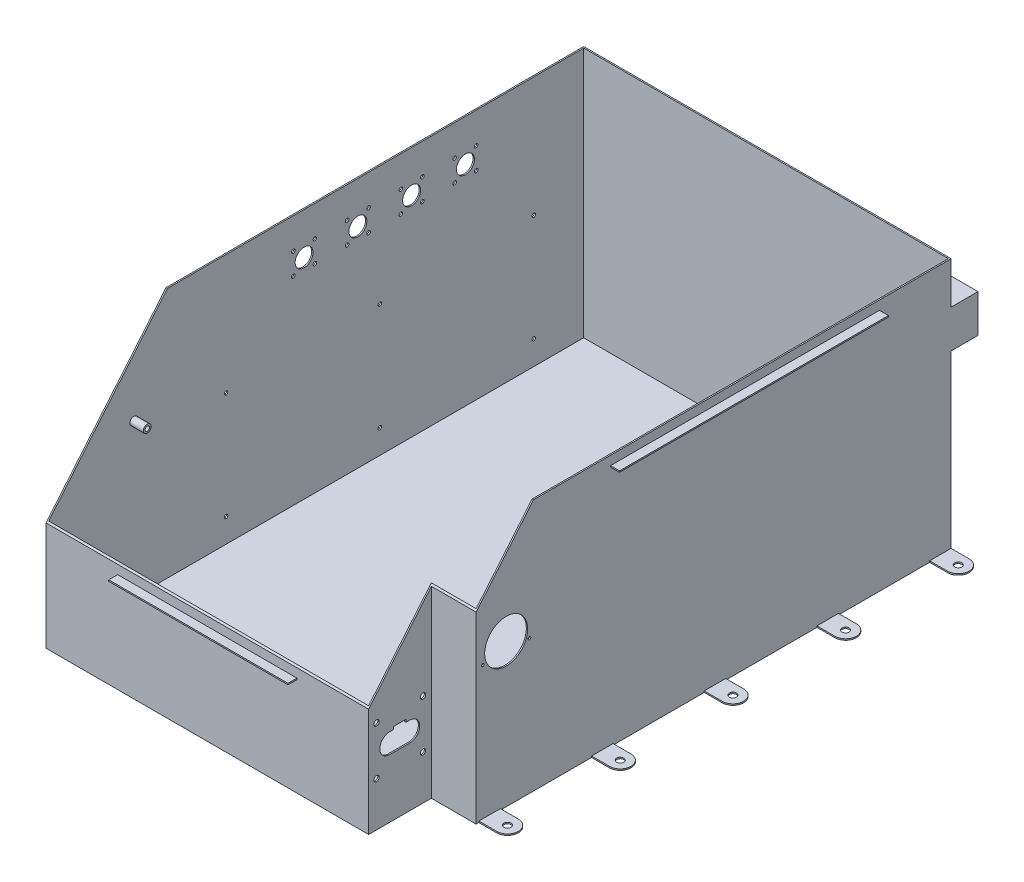
SolidWorks part; units mm, degrees
ref_plane "Front Plane" through (0, 0, 0) normal (0, 0, 1) x (1, 0, 0)
ref_plane "Top Plane" through (0, 0, 0) normal (0, 1, 0) x (1, 0, 0)
ref_plane "Right Plane" through (0, 0, 0) normal (1, 0, 0) x (0, 0, -1)
sketch "Sketch1" plane through (0, 0, 0) normal (0, 1, 0) x (1, 0, 0)
  line L1 (-205, 237.8263) -> (205, 237.8263)
  line L2 (-205, 237.8263) -> (-205, -362.1737)
  line L3 (-205, -362.1737) -> (155, -362.1737)
  line L4 (205, 237.8263) -> (205, -292.1737)
  line L6 (205, -292.1737) -> (155, -292.1737)
  line L7 (155, -292.1737) -> (155, -362.1737)
  line L8 (0, -55) -> (0, 55) construction
  point P1 (0, 237.8263)
  dimension "D1" = 600
  dimension "D2" = 410
  dimension "D5" = 70
  dimension "D6" = 50
extrude "Boss-Extrude1" add sketch "Sketch1" along normal blind 1.5
sketch "Sketch2" plane through (0, 1.5, 0) normal (0, 1, 0) x (1, 0, 0)
  line L60 (-203.5, 236.3263) -> (-203.5, -360.6737)
  line L61 (-203.5, -360.6737) -> (153.5, -360.6737)
  line L62 (153.5, -360.6737) -> (153.5, -290.6737)
  line L63 (153.5, -290.6737) -> (203.5, -290.6737)
  line L64 (203.5, -290.6737) -> (203.5, 236.3263)
  line L65 (203.5, 236.3263) -> (-203.5, 236.3263)
  line L66 (-205, 237.8263) -> (-205, -362.1737)
  line L67 (-205, -362.1737) -> (155, -362.1737)
  line L68 (155, -362.1737) -> (155, -292.1737)
  line L69 (155, -292.1737) -> (205, -292.1737)
  line L70 (205, -292.1737) -> (205, 237.8263)
  line L71 (205, 237.8263) -> (-205, 237.8263)
  line L72 (-205, 237.8263) -> (-205, -362.1737)
  line L73 (-205, -362.1737) -> (155, -362.1737)
  line L74 (155, -362.1737) -> (155, -292.1737)
  line L75 (155, -292.1737) -> (205, -292.1737)
  line L76 (205, -292.1737) -> (205, 237.8263)
  line L77 (205, 237.8263) -> (-205, 237.8263)
  dimension "D1" = 0
  dimension "D2" = 1.5
extrude "Boss-Extrude2" add sketch "Sketch2" along normal blind 280
sketch "Sketch3" plane through (-205, 0, 0) normal (-1, 0, 0) x (0, 0, 1)
  line L3 (362.1737, 281.5) -> (362.1737, 0) construction
  line L4 (362.1737, 121.1176) -> (228.1952, 281.5)
  line L6 (-237.8263, 281.5) -> (362.1737, 281.5) construction
  line L9 (362.1737, 281.5) -> (362.1737, 121.1176)
  line L10 (228.1952, 281.5) -> (362.1737, 281.5)
sketch "Sketch4" plane through (0, 0, -237.8263) normal (0, 0, -1) x (-1, 0, 0)
  line L0 (-205, 281.5) -> (-205, 0) construction
  line L1 (-205, 234.6761) -> (205, 234.6761)
  line L2 (-205, 234.6761) -> (-205, 192.2905)
  line L3 (-205, 192.2905) -> (205, 192.2905)
  line L4 (205, 234.6761) -> (205, 192.2905)
  line L5 (205, 281.5) -> (205, 0) construction
extrude "Boss-Extrude3" add sketch "Sketch4" along normal blind 30
extrude "Cut-Extrude1" cut sketch "Sketch3" against normal through all both and the other way through all
sketch "Sketch5" plane through (-205, 0, 0) normal (-1, 0, 0) x (0, 0, 1)
  line L0 (-116.3263, 223.1259) -> (-116.3263, 247.1259) construction
  line L5 (-116.3263, 223.1259) -> (-92.3263, 223.1259) construction
  line L6 (-116.3263, 247.1259) -> (-92.3263, 247.1259) construction
  line L7 (-92.3263, 223.1259) -> (-92.3263, 247.1259) construction
  line L8 (-116.3263, 223.1259) -> (-92.3263, 247.1259) construction
  line L9 (-116.3263, 247.1259) -> (-92.3263, 223.1259) construction
  line L10 (-56.3263, 223.1259) -> (-56.3263, 247.1259) construction
  line L11 (-56.3263, 223.1259) -> (-32.3263, 223.1259) construction
  line L12 (-56.3263, 247.1259) -> (-32.3263, 247.1259) construction
  line L13 (-32.3263, 223.1259) -> (-32.3263, 247.1259) construction
  line L14 (-56.3263, 223.1259) -> (-32.3263, 247.1259) construction
  line L15 (-56.3263, 247.1259) -> (-32.3263, 223.1259) construction
  line L16 (3.6737, 223.1259) -> (3.6737, 247.1259) construction
  line L17 (3.6737, 223.1259) -> (27.6737, 223.1259) construction
  line L18 (3.6737, 247.1259) -> (27.6737, 247.1259) construction
  line L19 (27.6737, 223.1259) -> (27.6737, 247.1259) construction
  line L20 (3.6737, 223.1259) -> (27.6737, 247.1259) construction
  line L21 (3.6737, 247.1259) -> (27.6737, 223.1259) construction
  line L22 (63.6737, 223.1259) -> (63.6737, 247.1259) construction
  line L23 (63.6737, 223.1259) -> (87.6737, 223.1259) construction
  line L24 (63.6737, 247.1259) -> (87.6737, 247.1259) construction
  line L25 (87.6737, 223.1259) -> (87.6737, 247.1259) construction
  line L26 (63.6737, 223.1259) -> (87.6737, 247.1259) construction
  line L27 (63.6737, 247.1259) -> (87.6737, 223.1259) construction
  line L28 (-236.3263, 281.5) -> (-236.3263, 1.5) construction
  circle A0 centre (-116.3263, 247.1259) radius 2
  circle A1 centre (-116.3263, 223.1259) radius 2
  circle A2 centre (-92.3263, 223.1259) radius 2
  circle A3 centre (-92.3263, 247.1259) radius 2
  circle A4 centre (-104.3263, 235.1259) radius 10
  circle A5 centre (-56.3263, 247.1259) radius 2
  circle A6 centre (-56.3263, 223.1259) radius 2
  circle A7 centre (-32.3263, 223.1259) radius 2
  circle A8 centre (-32.3263, 247.1259) radius 2
  circle A9 centre (-44.3263, 235.1259) radius 10
  circle A10 centre (3.6737, 247.1259) radius 2
  circle A11 centre (3.6737, 223.1259) radius 2
  circle A12 centre (27.6737, 223.1259) radius 2
  circle A13 centre (27.6737, 247.1259) radius 2
  circle A14 centre (15.6737, 235.1259) radius 10
  circle A15 centre (63.6737, 247.1259) radius 2
  circle A16 centre (63.6737, 223.1259) radius 2
  circle A17 centre (87.6737, 223.1259) radius 2
  circle A18 centre (87.6737, 247.1259) radius 2
  circle A19 centre (75.6737, 235.1259) radius 10
  point P9 (-104.3263, 235.1259)
  point P24 (-44.3263, 235.1259)
  point P38 (15.6737, 235.1259)
  point P52 (75.6737, 235.1259)
  dimension "D2" = 20
  dimension "D5" = 4
  dimension "D1" = 24
  dimension "D3" = 24
  dimension "D4" = 24
  dimension "D7" = 120
  dimension "D6" = 4
sketch "Sketch6" plane through (-203.5, 0, 0) normal (1, 0, 0) x (0, 0, -1)
  arc A0 (151.1392, 167.4539) -> (156.7272, 167.4539) centre (153.9332, 167.4539) ccw construction
  arc A1 (-68.8756, 167.4539) -> (-63.2876, 167.4539) centre (-66.0816, 167.4539) ccw construction
  arc A2 (-178.883, 167.4539) -> (-173.295, 167.4539) centre (-176.089, 167.4539) ccw construction
  arc A3 (151.1392, 167.4539) -> (156.7272, 167.4539) centre (153.9332, 167.4539) ccw
  arc A4 (-68.8756, 167.4539) -> (-63.2876, 167.4539) centre (-66.0816, 167.4539) ccw
  arc A5 (-178.883, 167.4539) -> (-173.295, 167.4539) centre (-176.089, 167.4539) ccw
  circle A6 centre (-176.089, 167.4539) radius 2.794
  circle A7 centre (-176.089, 167.4539) radius 4.5
  circle A8 centre (-64.4633, 167.4539) radius 4.5
  circle A9 centre (-64.4633, 167.4539) radius 2.794
  circle A10 centre (155.5515, 167.4539) radius 2.794
  circle A11 centre (155.5515, 167.4539) radius 4.5
  dimension "D1" = 9
extrude "Boss-Extrude4" [suppressed] add sketch "Sketch6" along normal blind 50 contours A4 A9 | A8 | A7 | A6 | A11 | A10
sketch "Sketch8" plane through (-203.5, 0, 0) normal (1, 0, 0) x (0, 0, -1)
  line L0 (236.3263, 1.5) -> (-360.6737, 1.5) construction
  line L1 (-360.6737, 122.9132) -> (-360.6737, 1.5) construction
  circle A0 centre (-265.6737, 172.2) radius 2.39
  circle A1 centre (-265.6737, 172.2) radius 4.39
  circle A2 centre (-265.6737, 16.5) radius 2.39
  circle A3 centre (-265.6737, 16.5) radius 4.39
  dimension "D3" = 4.78
  dimension "D4" = 2
  dimension "D1" = 155.7
  dimension "D2" = 15
  dimension "D5" = 95
extrude "Boss-Extrude5" add sketch "Sketch8" along normal blind 15
sketch "Sketch10" plane through (153.5, 0, 0) normal (-1, 0, 0) x (0, 0, 1)
  line L0 (316.1737, 86.5) -> (321.4237, 86.5) construction
  line L1 (316.1737, 66.5) -> (338.6737, 66.5) construction
  line L2 (338.6737, 76.5) -> (316.1737, 76.5) construction
  line L3 (360.6737, 1.5) -> (290.6737, 1.5) construction
  line L5 (321.4237, 86.5) -> (321.4237, 89.5) construction
  line L6 (321.4237, 89.5) -> (333.4237, 89.5) construction
  line L7 (333.4237, 86.5) -> (333.4237, 89.5) construction
  line L8 (360.6737, 122.9132) -> (360.6737, 1.5) construction
  line L9 (333.4237, 86.5) -> (338.6737, 86.5) construction
  line L10 (320.4237, 90.5) -> (334.4237, 90.5)
  line L11 (334.4237, 87.5) -> (334.4237, 90.5)
  line L12 (334.4237, 87.5) -> (338.6737, 87.5)
  line L13 (316.1737, 65.5) -> (338.6737, 65.5)
  line L14 (316.1737, 87.5) -> (320.4237, 87.5)
  line L15 (320.4237, 87.5) -> (320.4237, 90.5)
  line L17 (301.4737, 49.55) -> (353.3737, 49.55) construction
  line L18 (301.4737, 49.55) -> (301.4737, 103.45) construction
  line L19 (301.4737, 103.45) -> (353.3737, 103.45) construction
  line L20 (353.3737, 49.55) -> (353.3737, 103.45) construction
  line L21 (301.4737, 49.55) -> (353.3737, 103.45) construction
  line L22 (301.4737, 103.45) -> (353.3737, 49.55) construction
  arc A0 (316.1737, 86.5) -> (316.1737, 66.5) centre (316.1737, 76.5) ccw construction
  arc A1 (338.6737, 66.5) -> (338.6737, 86.5) centre (338.6737, 76.5) ccw construction
  arc A2 (338.6737, 65.5) -> (338.6737, 87.5) centre (338.6737, 76.5) ccw
  arc A3 (316.1737, 87.5) -> (316.1737, 65.5) centre (316.1737, 76.5) ccw
  circle A4 centre (301.4737, 103.45) radius 3
  circle A5 centre (353.3737, 103.45) radius 3
  circle A6 centre (301.4737, 49.55) radius 3
  circle A7 centre (353.3737, 49.55) radius 3
  point P12 (327.4237, 89.5)
  point P13 (327.4237, 76.5)
  point P26 (327.4237, 76.5)
  dimension "D1" = 65
  dimension "D2" = 22.5
  dimension "D6" = 20
  dimension "D10" = 6
  dimension "D3" = 22
  dimension "D4" = 12
  dimension "D5" = 3
  dimension "D8" = 51.9
  dimension "D9" = 53.9
  dimension "D7" = 1
extrude "Cut-Extrude2" cut sketch "Sketch10" against normal up to surface (1.5 mm away)
sketch "Sketch11" plane through (153.5, 0, 0) normal (-1, 0, 0) x (0, 0, 1)
  line L0 (298.4737, 103.43) -> (298.4737, 49.53) construction
  line L13 (316.1737, 66.5) -> (338.6737, 66.5) construction
  line L14 (316.1737, 86.5) -> (321.4237, 86.5) construction
  line L15 (316.1737, 66.5) -> (338.6737, 66.5)
  line L19 (316.1737, 86.5) -> (318.4237, 86.5)
  line L20 (334.4237, 90.5) -> (320.4237, 90.5)
  line L21 (334.4237, 90.5) -> (320.4237, 90.5)
  line L22 (334.4237, 87.5) -> (334.4237, 90.5)
  line L23 (334.4237, 87.5) -> (334.4237, 90.5)
  line L28 (330.4237, 86.5) -> (321.4237, 86.5)
  line L29 (316.2509, 66) -> (338.7144, 66)
  line L30 (330.9237, 86) -> (320.7529, 86)
  line L31 (330.9237, 86) -> (330.9237, 91)
  line L32 (330.9237, 91) -> (317.9237, 91)
  line L33 (317.9237, 91) -> (317.9237, 87)
  line L34 (316.2509, 87) -> (317.9237, 87)
  line L36 (298.4737, 103.43) -> (350.3737, 103.43) construction
  line L43 (334.4237, 90.5) -> (320.4237, 90.5)
  line L44 (334.4237, 90.5) -> (320.4237, 90.5)
  line L45 (334.4237, 87.5) -> (334.4237, 90.5)
  line L46 (334.4237, 87.5) -> (334.4237, 90.5)
  line L47 (338.6737, 87.5) -> (334.4237, 87.5)
  line L48 (338.6737, 87.5) -> (334.4237, 87.5)
  line L49 (316.1737, 65.5) -> (338.6737, 65.5)
  line L50 (316.1737, 65.5) -> (338.6737, 65.5)
  line L51 (320.4237, 87.5) -> (316.1737, 87.5)
  line L52 (320.4237, 87.5) -> (316.1737, 87.5)
  line L53 (320.4237, 90.5) -> (320.4237, 87.5)
  line L54 (320.4237, 90.5) -> (320.4237, 87.5)
  line L55 (334.4237, 90.5) -> (320.4237, 90.5)
  line L56 (334.4237, 90.5) -> (320.4237, 90.5)
  line L57 (334.4237, 87.5) -> (334.4237, 90.5)
  line L58 (334.4237, 87.5) -> (334.4237, 90.5)
  line L59 (338.6737, 87.5) -> (334.4237, 87.5)
  line L60 (338.6737, 87.5) -> (334.4237, 87.5)
  line L61 (316.1737, 65.5) -> (338.6737, 65.5)
  line L62 (316.1737, 65.5) -> (338.6737, 65.5)
  line L63 (320.4237, 87.5) -> (316.1737, 87.5)
  line L64 (320.4237, 87.5) -> (316.1737, 87.5)
  line L65 (320.4237, 90.5) -> (320.4237, 87.5)
  line L66 (320.4237, 90.5) -> (320.4237, 87.5)
  line L67 (330.4237, 86.5) -> (330.4237, 90.5) construction
  line L68 (330.4237, 90.5) -> (318.4237, 90.5) construction
  line L69 (318.4237, 90.5) -> (318.4237, 86.5) construction
  line L70 (338.6737, 87.5) -> (334.4237, 87.5)
  line L71 (338.6737, 87.5) -> (334.4237, 87.5)
  line L72 (316.1737, 65.5) -> (338.6737, 65.5)
  line L73 (316.1737, 65.5) -> (338.6737, 65.5)
  line L74 (320.4237, 87.5) -> (316.1737, 87.5)
  line L75 (320.4237, 87.5) -> (316.1737, 87.5)
  line L76 (320.4237, 90.5) -> (320.4237, 87.5)
  line L77 (320.4237, 90.5) -> (320.4237, 87.5)
  arc A4 (338.7144, 66) -> (320.7529, 86) centre (336.1498, 81.7622) ccw
  arc A5 (338.6737, 65.5) -> (338.6737, 87.5) centre (338.6737, 76.5) ccw
  arc A7 (338.6737, 65.5) -> (338.6737, 87.5) centre (338.6737, 76.5) ccw
  arc A9 (316.2509, 87) -> (316.2509, 66) centre (312.9721, 76.5) ccw
  circle A10 centre (298.4737, 103.43) radius 3
  circle A11 centre (298.4737, 49.53) radius 3
  circle A12 centre (350.3737, 103.43) radius 3
  circle A13 centre (350.3737, 49.53) radius 3
  arc A16 (338.6737, 66.5) -> (321.4237, 86.5) centre (336.1498, 81.7622) ccw construction
  arc A17 (338.6737, 65.5) -> (338.6737, 87.5) centre (338.6737, 76.5) ccw
  arc A18 (316.1737, 87.5) -> (316.1737, 65.5) centre (316.1737, 76.5) ccw
  arc A19 (316.1737, 87.5) -> (316.1737, 65.5) centre (316.1737, 76.5) ccw
  arc A20 (316.1737, 86.5) -> (316.1737, 66.5) centre (312.9721, 76.5) ccw construction
  arc A21 (338.6737, 65.5) -> (338.6737, 87.5) centre (338.6737, 76.5) ccw
  arc A22 (316.1737, 87.5) -> (316.1737, 65.5) centre (316.1737, 76.5) ccw
  arc A23 (316.1737, 87.5) -> (316.1737, 65.5) centre (316.1737, 76.5) ccw
  arc A24 (338.6737, 65.5) -> (338.6737, 87.5) centre (338.6737, 76.5) ccw
  arc A25 (338.6737, 65.5) -> (338.6737, 87.5) centre (338.6737, 76.5) ccw
  arc A26 (316.1737, 87.5) -> (316.1737, 65.5) centre (316.1737, 76.5) ccw
  arc A27 (316.1737, 87.5) -> (316.1737, 65.5) centre (316.1737, 76.5) ccw
  dimension "D5" = 6
  dimension "D6" = 51.9
  dimension "D7" = 53.9
  dimension "D1" = 0
  dimension "D2" = 0
  dimension "D3" = 0
  dimension "D4" = 0.5
extrude "Cut-Extrude3" [suppressed] cut sketch "Sketch11" against normal through all
sketch "Sketch14" plane through (153.5, 0, 0) normal (-1, 0, 0) x (0, 0, 1)
  line L0 (362.1737, 121.1176) -> (362.1737, 0) construction
  line L1 (362.1737, 0) -> (292.1737, 0) construction
  circle A0 centre (297.2737, 103.43) radius 3
  circle A1 centre (349.1737, 103.43) radius 3
  circle A2 centre (349.1737, 49.53) radius 3
  circle A3 centre (297.2737, 49.53) radius 3
  dimension "D5" = 6
  dimension "D1" = 51.9
  dimension "D2" = 53.9
  dimension "D3" = 13
  dimension "D4" = 103.43
extrude "Cut-Extrude4" [suppressed] cut sketch "Sketch14" against normal up to surface (1.5 mm away)
sketch "Sketch15" plane through (203.5, 0, 0) normal (-1, 0, 0) x (0, 0, 1)
  line L1 (-151.3263, 252.1363) -> (-136.3263, 252.1363)
  line L2 (-151.3263, 252.1363) -> (-151.3263, 250.6363)
  line L3 (-151.3263, 250.6363) -> (-136.3263, 250.6363)
  line L4 (-136.3263, 252.1363) -> (-136.3263, 250.6363)
  line L5 (-236.3263, 281.5) -> (-236.3263, 1.5) construction
  line L6 (126.6737, 252.1363) -> (146.6737, 252.1363)
  line L7 (126.6737, 250.6363) -> (146.6737, 250.6363)
  line L8 (126.6737, 252.1363) -> (126.6737, 250.6363)
  line L9 (146.6737, 252.1363) -> (146.6737, 250.6363)
  dimension "D1" = 1.5
  dimension "D2" = 15
  dimension "D3" = 85
  dimension "D4" = 363
  dimension "D5" = 20
extrude "Boss-Extrude6" add sketch "Sketch15" along normal blind 13
ref_plane "Plane1" through (0, 0, -131.3263) normal (0, 0, -1) x (-1, 0, 0)
sketch "Sketch17" plane through (0, 0, -136.3263) normal (0, 0, 1) x (1, 0, 0)
  line L0 (203.5, 250.6363) -> (203.5, 235.6363)
  line L1 (203.5, 281.5) -> (203.5, 206.7085) construction
  line L2 (203.5, 235.6363) -> (190.5, 250.6363)
  line L3 (190.5, 250.6363) -> (203.5, 250.6363)
  dimension "D1" = 15
extrude "Boss-Extrude7" add sketch "Sketch17" against normal blind 1.5
ref_plane "Plane2" through (0, 0, 126.6737) normal (0, 0, 1) x (1, 0, 0)
sketch "Sketch18" plane through (0, 0, 126.6737) normal (0, 0, 1) x (1, 0, 0)
  line L0 (203.5, 250.6363) -> (203.5, 235.6363)
  line L1 (203.5, 281.5) -> (203.5, 206.7085) construction
  line L2 (203.5, 235.6363) -> (190.5, 250.6363)
  line L3 (190.5, 250.6363) -> (203.5, 250.6363)
  dimension "D1" = 15
extrude "Boss-Extrude8" add sketch "Sketch18" along normal blind 1.5
sketch "Sketch20" plane through (0, 252.1363, 0) normal (0, 1, 0) x (1, 0, 0)
  line L1 (190.5, 151.3263) -> (203.5, 151.3263) construction
  line L2 (190.5, 136.3263) -> (190.5, 151.3263) construction
  line L3 (190.5, -146.6737) -> (203.5, -146.6737) construction
  line L4 (190.5, -146.6737) -> (190.5, -126.6737) construction
  circle A0 centre (198, 144.3263) radius 2.4159
  circle A1 centre (200.5, -139.6737) radius 2
  dimension "D3" = 4
  dimension "D1" = 7
  dimension "D2" = 7.5
  dimension "D4" = 7
  dimension "D5" = 10
extrude "Cut-Extrude5" cut sketch "Sketch20" against normal up to surface (1.5 mm away) up to face at (197, 250.6363, -144.5763)
extrude "Cut-Extrude7" cut sketch "Sketch5" against normal up to surface (1.5 mm away) up to face at (-203.5, 16.5, 261.2837)
sketch "Sketch21" plane through (0, 0, -237.8263) normal (0, 0, -1) x (-1, 0, 0)
  line L0 (-205, 281.5) -> (205, 281.5) construction
  line L1 (-150, 271.5) -> (150, 271.5)
  line L2 (-150, 271.5) -> (-150, 270)
  line L3 (-150, 270) -> (150, 270)
  line L4 (150, 271.5) -> (150, 270)
  point P6 (0, 281.5)
  point P7 (0, 271.5)
  dimension "D1" = 1.5
  dimension "D2" = 300
  dimension "D3" = 10
extrude "Boss-Extrude9" add sketch "Sketch21" along normal blind 10
sketch "Sketch22" plane through (-205, 0, 0) normal (-1, 0, 0) x (0, 0, 1)
  line L0 (-237.8263, 281.5) -> (228.1952, 281.5) construction
  line L1 (-157.8263, 271.5) -> (142.1737, 271.5)
  line L2 (-157.8263, 271.5) -> (-157.8263, 270)
  line L3 (-157.8263, 270) -> (142.1737, 270)
  line L4 (142.1737, 271.5) -> (142.1737, 270)
  line L5 (-237.8263, 281.5) -> (-237.8263, 234.6761) construction
  dimension "D1" = 1.5
  dimension "D2" = 10
  dimension "D3" = 80
  dimension "D4" = 300
extrude "Boss-Extrude10" add sketch "Sketch22" along normal blind 10
ref_plane "Plane3" through (0, 0, -77.8263) normal (0, 0, -1) x (-1, 0, 0)
sketch "Sketch23" plane through (0, 0, -77.8263) normal (0, 0, -1) x (-1, 0, 0)
  line L0 (215, 270) -> (205, 270) construction
  line L1 (215, 270) -> (205, 270)
  line L2 (215, 270) -> (205, 260)
  line L3 (205, 281.5) -> (205, 234.6761) construction
  line L4 (205, 260) -> (205, 270)
  dimension "D1" = 10
extrude "Boss-Extrude11" add sketch "Sketch23" along normal mid plane 1.5
ref_plane "Plane4" through (0, 0, 52.1737) normal (0, 0, 1) x (1, 0, 0)
sketch "Sketch24" plane through (0, 0, 52.1737) normal (0, 0, 1) x (1, 0, 0)
  line L6 (-215, 270) -> (-205, 260)
  line L7 (-205, 260) -> (-205, 270)
  line L8 (-205, 270) -> (-215, 270)
  line L9 (-215, 270) -> (-205, 260)
  line L10 (-205, 260) -> (-205, 270)
  line L11 (-205, 270) -> (-215, 270)
  dimension "D1" = 0
extrude "Boss-Extrude12" add sketch "Sketch24" along normal mid plane 1.5
ref_plane "Plane5" through (100, 0, 0) normal (1, 0, 0) x (0, 0, -1)
sketch "Sketch25" plane through (100, 0, 0) normal (1, 0, 0) x (0, 0, -1)
  line L0 (247.8263, 270) -> (237.8263, 270)
  line L1 (237.8263, 270) -> (237.8263, 260)
  line L2 (237.8263, 281.5) -> (237.8263, 234.6761) construction
  line L3 (237.8263, 260) -> (247.8263, 270)
  dimension "D1" = 10
extrude "Boss-Extrude13" add sketch "Sketch25" along normal mid plane 1.5
ref_plane "Plane6" through (-100, 0, 0) normal (-1, 0, 0) x (0, 0, 1)
sketch "Sketch26" plane through (-100, 0, 0) normal (-1, 0, 0) x (0, 0, 1)
  line L3 (-247.8263, 270) -> (-237.8263, 260)
  line L4 (-237.8263, 260) -> (-237.8263, 270)
  line L5 (-237.8263, 270) -> (-247.8263, 270)
  line L6 (-247.8263, 270) -> (-237.8263, 260)
  line L7 (-237.8263, 260) -> (-237.8263, 270)
  line L8 (-237.8263, 270) -> (-247.8263, 270)
  dimension "D1" = 0
extrude "Boss-Extrude14" add sketch "Sketch26" along normal mid plane 1.5
mirror "Mirror1" about plane through (0, 0, 0) normal (1, 0, 0) of "Boss-Extrude11", "Boss-Extrude12", "Boss-Extrude10"
sketch "Sketch27" plane through (0, 0, 362.1737) normal (0, 0, 1) x (1, 0, 0)
  line L0 (155, 121.1176) -> (-205, 121.1176) construction
  line L1 (-125, 111.1176) -> (75, 111.1176)
  line L2 (-125, 111.1176) -> (-125, 109.6176)
  line L3 (-125, 109.6176) -> (75, 109.6176)
  line L4 (75, 111.1176) -> (75, 109.6176)
  line L5 (155, 121.1176) -> (-205, 121.1176) construction
  point P6 (-25, 121.1176)
  point P7 (-25, 111.1176)
  dimension "D1" = 1.5
  dimension "D2" = 200
  dimension "D3" = 10
extrude "Boss-Extrude15" add sketch "Sketch27" along normal blind 10
ref_plane "Plane7" through (-95, 0, 0) normal (-1, 0, 0) x (0, 0, 1)
sketch "Sketch28" plane through (-95, 0, 0) normal (-1, 0, 0) x (0, 0, 1)
  line L0 (372.1737, 109.6176) -> (362.1737, 109.6176)
  line L1 (362.1737, 109.6176) -> (362.1737, 99.6176)
  line L2 (362.1737, 121.1176) -> (362.1737, 0) construction
  line L3 (362.1737, 99.6176) -> (372.1737, 109.6176)
  dimension "D1" = 10
extrude "Boss-Extrude16" add sketch "Sketch28" along normal mid plane 1.5
ref_plane "Plane8" through (45, 0, 0) normal (1, 0, 0) x (0, 0, -1)
sketch "Sketch29" plane through (45, 0, 0) normal (1, 0, 0) x (0, 0, -1)
  line L3 (-372.1737, 109.6176) -> (-362.1737, 99.6176)
  line L4 (-362.1737, 99.6176) -> (-362.1737, 109.6176)
  line L5 (-362.1737, 109.6176) -> (-372.1737, 109.6176)
  line L6 (-372.1737, 109.6176) -> (-362.1737, 99.6176)
  line L7 (-362.1737, 99.6176) -> (-362.1737, 109.6176)
  line L8 (-362.1737, 109.6176) -> (-372.1737, 109.6176)
  dimension "D1" = 0
extrude "Boss-Extrude17" add sketch "Sketch29" along normal mid plane 1.5
sketch "Sketch30" plane through (205, 0, 0) normal (1, 0, 0) x (0, 0, -1)
  line L1 (-292.1737, 0) -> (237.8263, 0) construction
  line L2 (-292.1737, 204.9129) -> (-292.1737, 0) construction
  circle A0 centre (-258.6737, 160) radius 24
  circle A1 centre (-284.6737, 150) radius 1.5
  circle A2 centre (-232.6737, 150) radius 1.5
  dimension "D1" = 48
  dimension "D2" = 3
  dimension "D3" = 3
  dimension "D4" = 26
  dimension "D5" = 10
  dimension "D6" = 26
  dimension "D7" = 10
  dimension "D8" = 160
  dimension "D9" = 33.5
extrude "Cut-Extrude8" cut sketch "Sketch30" against normal up to surface (1.5 mm away) up to face at (203.5, 246.1363, -141.8263)
sketch "Sketch31" plane through (0, 0, 0) normal (0, -1, 0) x (1, 0, 0)
  line L0 (205, -237.8263) -> (-205, -237.8263) construction
  line L1 (205, -213.8263) -> (225, -213.8263)
  line L2 (205, -213.8263) -> (205, -237.8263)
  line L3 (205, -237.8263) -> (225, -237.8263)
  line L4 (225, -213.8263) -> (225, -237.8263)
  line L64 (205, 228.1952) -> (205, -237.8263) construction
  line L65 (205, -88.0763) -> (225, -88.0763)
  line L66 (205, -88.0763) -> (205, -112.0763)
  line L67 (205, -112.0763) -> (225, -112.0763)
  line L68 (225, -88.0763) -> (225, -112.0763)
  line L69 (205, 37.6737) -> (225, 37.6737)
  line L70 (205, 37.6737) -> (205, 13.6737)
  line L71 (205, 13.6737) -> (225, 13.6737)
  line L72 (225, 37.6737) -> (225, 13.6737)
  line L73 (205, 163.4237) -> (225, 163.4237)
  line L74 (205, 163.4237) -> (205, 139.4237)
  line L75 (205, 139.4237) -> (225, 139.4237)
  line L76 (225, 163.4237) -> (225, 139.4237)
  line L77 (205, 289.1737) -> (225, 289.1737)
  line L78 (205, 289.1737) -> (205, 265.1737)
  line L79 (205, 265.1737) -> (225, 265.1737)
  line L80 (225, 289.1737) -> (225, 265.1737)
  circle A0 centre (225, -225.8263) radius 12
  circle A1 centre (225, -225.8263) radius 4
  circle A30 centre (225, -100.0763) radius 12
  circle A31 centre (225, -100.0763) radius 4
  circle A32 centre (225, 25.6737) radius 12
  circle A33 centre (225, 25.6737) radius 4
  circle A34 centre (225, 151.4237) radius 12
  circle A35 centre (225, 151.4237) radius 4
  circle A36 centre (225, 277.1737) radius 12
  circle A37 centre (225, 277.1737) radius 4
  point P76 (0, 0)
  dimension "D3" = 8
  dimension "D1" = 24
  dimension "D2" = 20
  dimension "D5" = 101.75
  dimension "D4" = 5
extrude "Boss-Extrude18" add sketch "Sketch31" against normal blind 1.5 separate body
sketch "Sketch33" plane through (-205, 0, 0) normal (-1, 0, 0) x (0, 0, 1)
  line L0 (-237.8263, 192.2905) -> (-237.8263, 0) construction
  line L1 (-237.8263, 0) -> (362.1737, 0) construction
  circle A0 centre (-180.6263, 147.77) radius 2
  circle A1 centre (-180.6263, 28.39) radius 2
  circle A2 centre (-8.9263, 147.77) radius 2
  circle A3 centre (-8.9263, 28.39) radius 2
  circle A4 centre (162.7737, 147.77) radius 2
  circle A5 centre (162.7737, 28.39) radius 2
  dimension "D3" = 4
  dimension "D1" = 57.2
  dimension "D2" = 119.38
  dimension "D4" = 28.39
  dimension "D5" = 3
extrude "Cut-Extrude9" cut sketch "Sketch33" against normal up to surface (1.5 mm away) up to face at (-203.5, 223.1259, 25.6737)
mirror "Mirror2" about plane through (0, 0, 0) normal (1, 0, 0) of "Boss-Extrude18"
